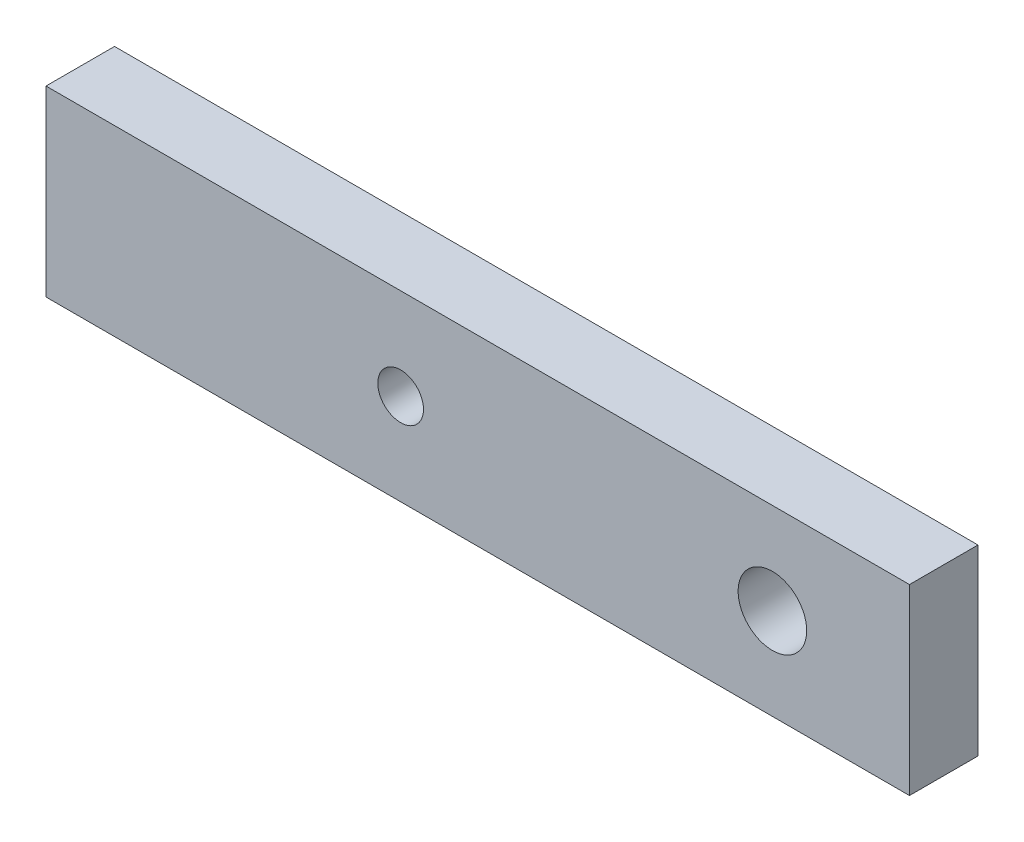
SolidWorks part; units mm, degrees
ref_plane "Спереди" through (0, 0, 0) normal (0, 0, 1) x (1, 0, 0)
ref_plane "Сверху" through (0, 0, 0) normal (0, 1, 0) x (1, 0, 0)
ref_plane "Справа" through (0, 0, 0) normal (1, 0, 0) x (0, 0, -1)
sketch "Ескіз" plane through (0, 0, 0) normal (0, 0, 1) x (1, 0, 0)
  line L0 (-1890, 200) -> (0, 200) construction
  line L1 (0, 0) -> (-1890, 0)
  line L2 (0, 0) -> (0, 400)
  line L3 (0, 400) -> (-1890, 400)
  line L4 (-1890, 0) -> (-1890, 400)
  circle A0 centre (-300, 200) radius 75
  circle A1 centre (-1113.7095, 200) radius 50
  dimension "Діаметр отвору" = 150
  dimension "Діаметр отвору під шатун" = 100
  dimension "Висота" = 400
  dimension "Довжина" = 1890
  dimension "Координата отвору" = 300
  dimension "Радіус" = 813.7095
extrude "Профіль" add sketch "Ескіз" along normal blind 150
equation "\"Довжина@Ескіз\" = 1890.0"
equation "\"Радіус@Ескіз\" = 813.709502285"
equation "\"Ширина@Профіль\" = 150.0"
equation "\"Висота@Ескіз\"= 400"
equation "\"Координата отвору@Ескіз\" = 300"
